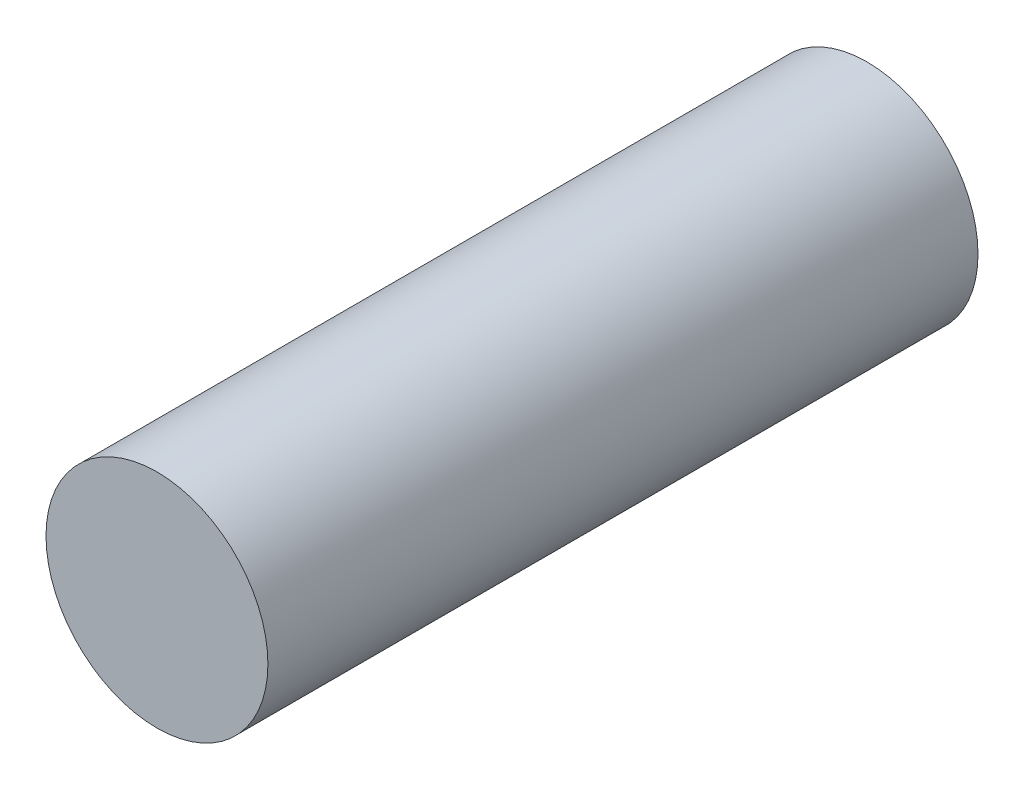
SolidWorks part; units mm, degrees
ref_plane "Спереди" through (0, 0, 0) normal (0, 0, 1) x (1, 0, 0)
ref_plane "Сверху" through (0, 0, 0) normal (0, 1, 0) x (1, 0, 0)
ref_plane "Справа" through (0, 0, 0) normal (1, 0, 0) x (0, 0, -1)
sketch "Эскиз1" plane through (0, 0, 0) normal (0, 0, 1) x (1, 0, 0)
  circle A0 centre (0, 0) radius 5
  dimension "D1" = 10
extrude "Бобышка-Вытянуть1" add sketch "Эскиз1" along normal blind 32 contours A0
